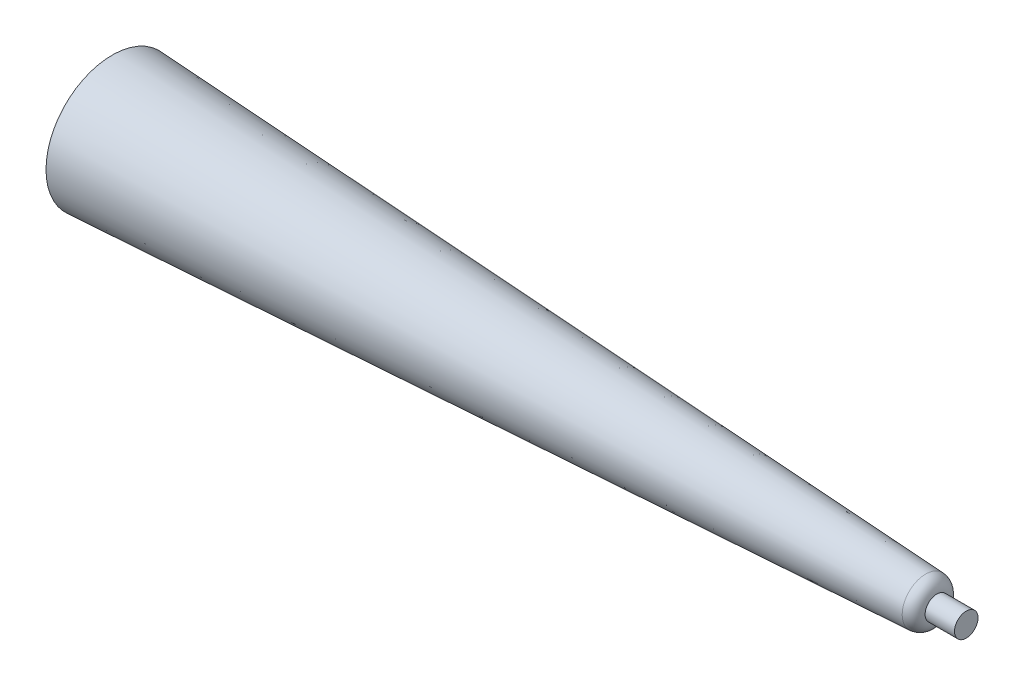
SolidWorks part; units mm, degrees
ref_plane "Front Plane" through (0, 0, 0) normal (0, 0, 1) x (1, 0, 0)
ref_plane "Top Plane" through (0, 0, 0) normal (0, 1, 0) x (1, 0, 0)
ref_plane "Right Plane" through (0, 0, 0) normal (1, 0, 0) x (0, 0, -1)
sketch "Sketch4" plane through (0, 0, 0) normal (0, 0, 1) x (1, 0, 0)
  line L0 (-54.8673, -6.1468) -> (-17.9737, -6.1468)
  line L1 (-17.9737, -6.1468) -> (-17.9737, -5.6388)
  line L2 (-17.9737, -5.6388) -> (-19.2437, -5.6388)
  line L3 (-19.7258, -5.1308) -> (-54.8673, -3.2891)
  line L4 (-54.8673, -3.2891) -> (-54.8673, -6.1468)
  arc A0 (-19.2437, -5.6388) -> (-19.7258, -5.1308) centre (-19.7524, -5.6388) ccw
  dimension "D1" = 3
  dimension "D2" = 0.508
  dimension "D3" = 1.016
  dimension "D4" = 1.27
  dimension "D5" = 17.9737
  dimension "D6" = 5.6388
revolve "Revolve1" add sketch "Sketch4" angle 360 about L0
